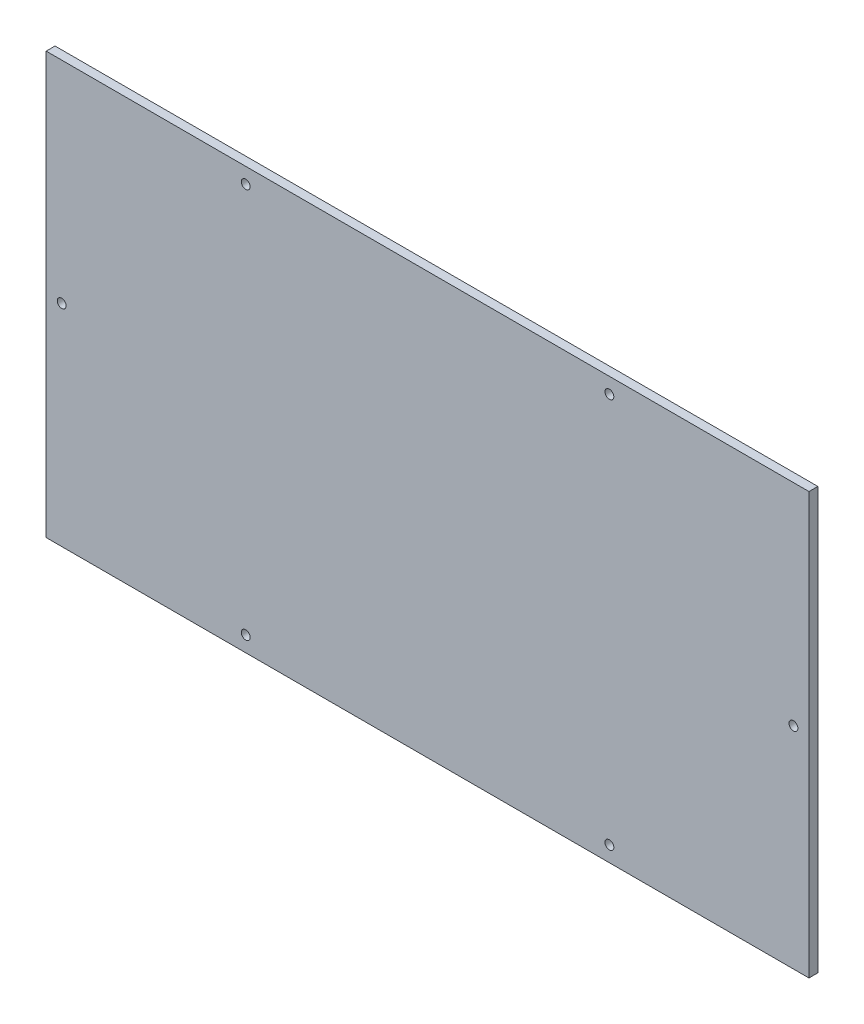
SolidWorks part; units mm, degrees
ref_plane "Piano frontale" through (0, 0, 0) normal (0, 0, 1) x (1, 0, 0)
ref_plane "Piano superiore" through (0, 0, 0) normal (0, 1, 0) x (1, 0, 0)
ref_plane "Piano destro" through (0, 0, 0) normal (1, 0, 0) x (0, 0, -1)
sketch "Schizzo1" plane through (0, 0, 0) normal (0, 0, 1) x (1, 0, 0)
  line L0 (-172, 351.6275) -> (-172, -66.2585) construction
  line L1 (0, 0) -> (-344, 0)
  line L2 (0, 0) -> (0, 190)
  line L3 (0, 190) -> (-344, 190)
  line L4 (-344, 0) -> (-344, 190)
  line L5 (-387.9788, 95) -> (120.8821, 95) construction
  circle A0 centre (-90, 183) radius 2
  circle A1 centre (-7, 95) radius 2
  circle A2 centre (-254, 183) radius 2
  circle A3 centre (-337, 95) radius 2
  circle A4 centre (-254, 7) radius 2
  circle A7 centre (-90, 7) radius 2
  point P9 (-172, 95)
  dimension "D3" = 4
  dimension "D1" = 344
  dimension "314" = 190
  dimension "D4" = 7
  dimension "D5" = 90
  dimension "D6" = 7
extrude "Estrusione-Estrusione1" add sketch "Schizzo1" along normal blind 4
